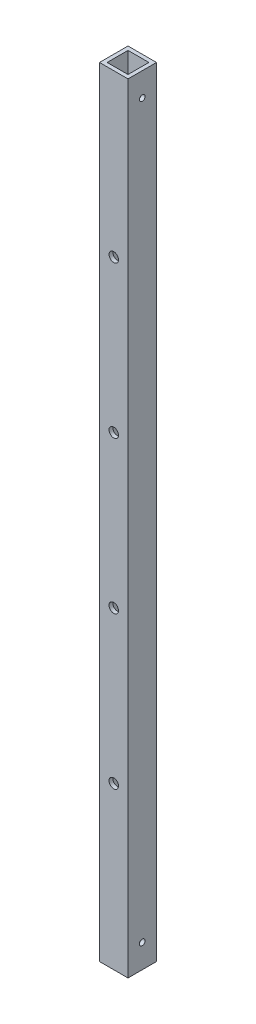
SolidWorks part; units mm, degrees
material "6061 合金"
ref_plane "前视基准面" through (0, 0, 0) normal (0, 0, 1) x (1, 0, 0)
ref_plane "上视基准面" through (0, 0, 0) normal (0, 1, 0) x (1, 0, 0)
ref_plane "右视基准面" through (0, 0, 0) normal (1, 0, 0) x (0, 0, -1)
sketch "草图1" plane through (0, 0, 0) normal (0, 1, 0) x (1, 0, 0)
  line L1 (-7.5, 7.5) -> (7.5, 7.5)
  line L2 (-7.5, 7.5) -> (-7.5, -7.5)
  line L3 (-7.5, -7.5) -> (7.5, -7.5)
  line L4 (7.5, 7.5) -> (7.5, -7.5)
  line L5 (-7.5, 7.5) -> (7.5, -7.5) construction
  line L6 (-7.5, -7.5) -> (7.5, 7.5) construction
  point P1 (0, 0)
extrude "凸台-拉伸1" add sketch "草图1" along normal blind 410
sketch "草图2" plane through (0, 410, 0) normal (0, 1, 0) x (1, 0, 0)
  line L1 (-5.5, 5.5) -> (5.5, 5.5)
  line L2 (-5.5, 5.5) -> (-5.5, -5.5)
  line L3 (-5.5, -5.5) -> (5.5, -5.5)
  line L4 (5.5, 5.5) -> (5.5, -5.5)
  line L5 (-5.5, 5.5) -> (5.5, -5.5) construction
  line L6 (-5.5, -5.5) -> (5.5, 5.5) construction
  point P0 (0, 0)
extrude "切除-拉伸1" cut sketch "草图2" against normal blind 410
sketch "草图3" plane through (0, 0, 7.5) normal (0, 0, 1) x (1, 0, 0)
  line L3 (-7.5, 410) -> (-7.5, 0) construction
  line L4 (7.5, 410) -> (-7.5, 410) construction
  line L5 (7.5, 0) -> (-7.5, 0) construction
  circle A0 centre (0, 85) radius 2.5
  circle A1 centre (0, 165) radius 2.5
  circle A2 centre (0, 245) radius 2.5
  circle A3 centre (0, 325) radius 2.5
  dimension "D8" = 5
  dimension "D9" = 5
  dimension "D10" = 5
  dimension "D13" = 5
  dimension "D2" = 85
  dimension "D3" = 80
  dimension "D4" = 85
  dimension "D5" = 80
  dimension "D6" = 7.5
  dimension "D7" = 7.5
  dimension "D11" = 7.5
  dimension "D12" = 7.5
extrude "切除-拉伸2" cut sketch "草图3" against normal blind 15
sketch "草图4" plane through (-7.5, 0, 0) normal (-1, 0, 0) x (0, 0, 1)
  line L0 (-7.5, 410) -> (7.5, 410) construction
  line L1 (7.5, 410) -> (7.5, 0) construction
  line L2 (-7.5, 0) -> (7.5, 0) construction
  circle A0 centre (0, 12.5) radius 1.5
  circle A1 centre (0, 397.5) radius 1.5
  dimension "D1" = 12.5
  dimension "D3" = 3
  dimension "D2" = 7.5
  dimension "D4" = 12.5
  dimension "D5" = 7.5
extrude "切除-拉伸3" cut sketch "草图4" against normal blind 15
